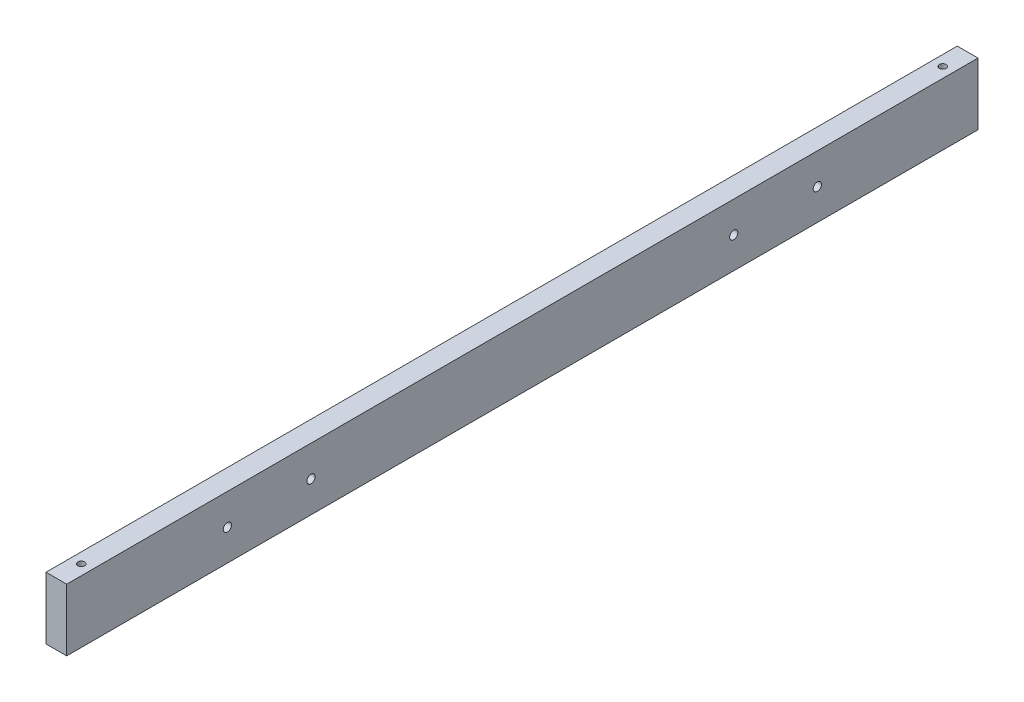
SolidWorks part; units mm, degrees
ref_plane "Front Plane" through (0, 0, 0) normal (0, 0, 1) x (1, 0, 0)
ref_plane "Top Plane" through (0, 0, 0) normal (0, 1, 0) x (1, 0, 0)
ref_plane "Right Plane" through (0, 0, 0) normal (1, 0, 0) x (0, 0, -1)
sketch "Sketch1" plane through (0, 0, 0) normal (0, 0, 1) x (1, 0, 0)
  line L1 (0, 0) -> (10, 0)
  line L2 (0, 0) -> (0, 30)
  line L3 (0, 30) -> (10, 30)
  line L4 (10, 0) -> (10, 30)
  dimension "D1" = 30
  dimension "D2" = 10
extrude "Boss-Extrude1" add sketch "Sketch1" along normal blind 440
sketch "Esquisse1" plane through (0, 30, 0) normal (0, 1, 0) x (1, 0, 0)
  line L0 (5, 0) -> (5, -440) construction
  line L1 (10, 0) -> (0, 0) construction
  line L2 (10, -440) -> (0, -440) construction
  circle A0 centre (5, -428) radius 1.65
  circle A1 centre (5, -12) radius 1.65
  dimension "D2" = 3.3
  dimension "D1" = 12
  dimension "D3" = 12
extrude "Enlèv. mat.-Extru.1" cut sketch "Esquisse1" against normal through all
sketch "Esquisse2" plane through (10, 0, 0) normal (1, 0, 0) x (0, 0, -1)
  line L0 (-220, 30) -> (-220, 0) construction
  line L1 (-440, 30) -> (0, 30) construction
  line L2 (-440, 0) -> (0, 0) construction
  line L3 (-362.425, 30) -> (-362.425, 0) construction
  line L4 (-77.575, 0) -> (-77.575, 30) construction
  line L5 (-440, 15) -> (0, 15) construction
  line L6 (-440, 0) -> (-440, 30) construction
  line L7 (0, 0) -> (0, 30) construction
  circle A0 centre (-362.425, 15) radius 2
  circle A1 centre (-77.575, 15) radius 2
  circle A2 centre (-322.04, 15) radius 2
  circle A3 centre (-117.96, 15) radius 2
  point P15 (-362.425, 15)
  dimension "D2" = 4
  dimension "D1" = 284.85
  dimension "D3" = 204.08
extrude "Enlèv. mat.-Extru.2" cut sketch "Esquisse2" against normal through all
